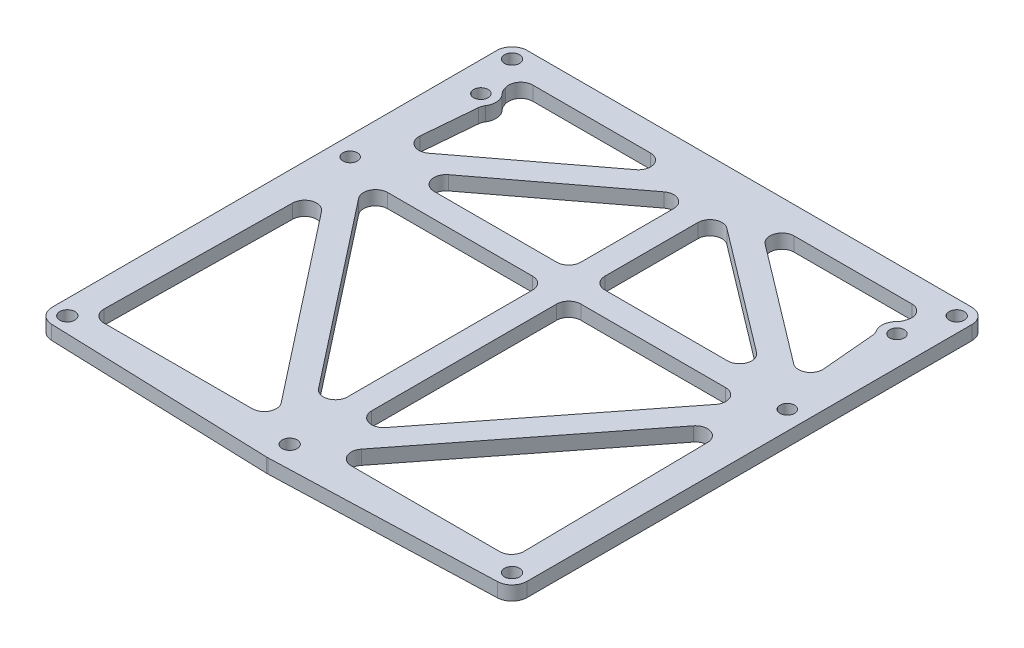
SolidWorks part; units mm, degrees
ref_plane "Front Plane" through (0, 0, 0) normal (0, 0, 1) x (1, 0, 0)
ref_plane "Top Plane" through (0, 0, 0) normal (0, 1, 0) x (1, 0, 0)
ref_plane "Right Plane" through (0, 0, 0) normal (1, 0, 0) x (0, 0, -1)
sketch "Sketch1" plane through (0, 0, 0) normal (0, 1, 0) x (1, 0, 0)
  line L0 (-43.8131, 37.2517) -> (-46.0269, 11.9483) construction
  line L1 (-50, -50) -> (50, -50) construction
  line L2 (-50, -50) -> (-50, 50) construction
  line L3 (-50, 50) -> (50, 50) construction
  line L4 (50, -50) -> (50, 50) construction
  line L5 (-50, -50) -> (50, 50) construction
  line L6 (-50, 50) -> (50, -50) construction
  line L7 (-46.0269, 11.9483) -> (-46.0269, 36.2261) construction
  line L8 (0, 0) -> (0, 21.5211) construction
  circle A0 centre (-46.825, -46.825) radius 1.5875
  circle A1 centre (-46.825, 46.825) radius 1.5875
  circle A2 centre (46.825, 46.825) radius 1.5875
  circle A3 centre (46.825, -46.825) radius 1.5875
  circle A4 centre (-43.8131, 37.2517) radius 1.524
  circle A5 centre (-46.0269, 11.9483) radius 1.524
  circle A6 centre (46.0269, 11.9483) radius 1.524
  circle A7 centre (43.8131, 37.2517) radius 1.524
  circle A8 centre (0, -46.825) radius 1.5875
  point P0 (0, 0)
  point P17 (0, 0)
  point P20 (-44.92, 24.6)
  dimension "D3" = 3.175
  dimension "D4" = 3.175
  dimension "D8" = 3.048
  dimension "D11" = 3.175
  dimension "D12" = 3.175
  dimension "D1" = 100
  dimension "D2" = 100
  dimension "D6" = 5
  dimension "D7" = 25.4
  dimension "D9" = 5.08
  dimension "D10" = 25.4
  dimension "D5" = 4
sketch "Sketch2" plane through (0, 0, 0) normal (0, 1, 0) x (1, 0, 0)
  line L0 (0.1615, -51.5848) -> (46.9326, -49.9982)
  line L1 (-0.1615, -51.5848) -> (-46.9326, -49.9982)
  line L2 (-46.825, 50) -> (46.825, 50)
  line L3 (50, 46.825) -> (50, -46.825)
  line L4 (-50, -46.825) -> (-50, 46.825)
  circle A0 centre (46.825, 46.825) radius 1.5875 construction
  circle A1 centre (43.8131, 37.2517) radius 1.524 construction
  circle A2 centre (46.0269, 11.9483) radius 1.524 construction
  circle A3 centre (46.825, -46.825) radius 1.5875 construction
  circle A4 centre (0, -46.825) radius 1.5875 construction
  circle A5 centre (-46.825, -46.825) radius 1.5875 construction
  circle A6 centre (-46.0269, 11.9483) radius 1.524 construction
  circle A7 centre (-43.8131, 37.2517) radius 1.524 construction
  circle A8 centre (-46.825, 46.825) radius 1.5875 construction
  circle A9 centre (46.825, 46.825) radius 1.5875
  circle A10 centre (43.8131, 37.2517) radius 1.524
  circle A11 centre (46.0269, 11.9483) radius 1.524
  circle A12 centre (46.825, -46.825) radius 1.5875
  circle A13 centre (0, -46.825) radius 1.5875
  circle A14 centre (-46.825, -46.825) radius 1.5875
  circle A15 centre (-46.0269, 11.9483) radius 1.524
  circle A16 centre (-43.8131, 37.2517) radius 1.524
  circle A17 centre (-46.825, 46.825) radius 1.5875
  circle A18 centre (-46.825, 46.825) radius 3.175
  circle A19 centre (-43.8131, 37.2517) radius 3.175
  circle A20 centre (-46.0269, 11.9483) radius 3.175
  circle A21 centre (-46.825, -46.825) radius 3.175
  circle A23 centre (46.825, -46.825) radius 3.175
  circle A24 centre (46.0269, 11.9483) radius 3.175
  circle A25 centre (43.8131, 37.2517) radius 3.175
  circle A26 centre (46.825, 46.825) radius 3.175
  circle A27 centre (0, -46.825) radius 4.7625
  dimension "D1" = 6.35
  dimension "D2" = 9.525
extrude "Boss-Extrude2" add sketch "Sketch2" along normal blind 2.9718 contours A27 L0 A23 L3 A26 L2 A18 L4 A21 L1 A19 A20 A24 A25 | A21 A14 | A27 A13 | A23 A12 | A24 A11 | A25 A10 | A26 A9 | A19 A16 | A18 A17 | A20 A15
sketch "Sketch3" plane through (0, 0, 0) normal (0, 1, 0) x (1, 0, 0)
  line L0 (-46.825, -46.825) -> (0, -46.825) construction
  line L1 (0, -46.825) -> (46.825, -46.825) construction
  line L2 (46.825, -46.825) -> (46.0269, 11.9483) construction
  line L3 (46.0269, 11.9483) -> (46.825, 46.825) construction
  line L4 (46.825, 46.825) -> (-46.825, 46.825) construction
  line L5 (-46.825, 46.825) -> (-46.0269, 11.9483) construction
  line L6 (-46.0269, 11.9483) -> (-46.825, -46.825) construction
  line L7 (0, -46.825) -> (-46.0269, 11.9483) construction
  line L8 (-46.0269, 11.9483) -> (46.0269, 11.9483) construction
  line L9 (46.0269, 11.9483) -> (0, -46.825) construction
  line L10 (43.8131, 37.2517) -> (46.825, 46.825) construction
  line L11 (-46.825, 46.825) -> (-43.8131, 37.2517) construction
  line L12 (46.0269, 11.9483) -> (0, 46.825) construction
  line L13 (0, 46.825) -> (-46.0269, 11.9483) construction
  line L14 (43.8131, 37.2517) -> (46.0269, 11.9483) construction
  line L15 (-46.0269, 11.9483) -> (-43.8131, 37.2517) construction
  line L16 (0, 11.9483) -> (0, -46.825) construction
  line L17 (0, 46.825) -> (0, 11.9483) construction
  line L18 (46.825, 49.365) -> (-46.825, 49.365)
  line L19 (-2.54, 46.825) -> (-2.54, 11.9483)
  line L20 (47.5609, 13.9728) -> (0, 50.0118)
  line L21 (0, 50.0118) -> (-47.5609, 13.9728)
  line L22 (-46.0269, 9.4083) -> (46.0269, 9.4083)
  line L23 (1.9998, -45.2589) -> (-44.0271, 13.5144)
  line L24 (-2.54, 11.9483) -> (-2.54, -46.825)
  line L25 (44.0271, 13.5144) -> (-1.9998, -45.2589)
  line L26 (0, -49.365) -> (49.3997, -49.365)
  line L27 (49.3997, -49.365) -> (48.5666, 11.9828)
  line L28 (-48.5666, 11.9828) -> (-49.3997, -49.365)
  line L29 (-49.3997, -49.365) -> (0, -49.365)
  line L30 (41.2828, 37.0303) -> (43.4965, 11.727)
  line L31 (48.5662, 11.8902) -> (49.3643, 46.7669)
  line L32 (46.236, 36.4894) -> (49.2479, 46.0627)
  line L33 (-49.2479, 46.0627) -> (-46.236, 36.4894)
  line L34 (-49.3643, 46.7669) -> (-48.5662, 11.8902)
  line L35 (-43.4965, 11.727) -> (-41.2828, 37.0303)
  line L36 (46.825, 44.285) -> (-46.825, 44.285)
  line L37 (2.54, 46.825) -> (2.54, 11.9483)
  line L38 (44.4929, 9.9239) -> (0, 43.6382)
  line L39 (0, 43.6382) -> (-44.4929, 9.9239)
  line L40 (-46.0269, 14.4883) -> (46.0269, 14.4883)
  line L41 (-1.9998, -48.3911) -> (-48.0266, 10.3823)
  line L42 (2.54, 11.9483) -> (2.54, -46.825)
  line L43 (48.0266, 10.3823) -> (1.9998, -48.3911)
  line L44 (0, -44.285) -> (44.2503, -44.285)
  line L45 (44.2503, -44.285) -> (43.4871, 11.9138)
  line L46 (-43.4871, 11.9138) -> (-44.2503, -44.285)
  line L47 (-44.2503, -44.285) -> (0, -44.285)
  line L48 (46.3435, 37.473) -> (48.5572, 12.1697)
  line L49 (43.4875, 12.0064) -> (44.2857, 46.8831)
  line L50 (41.3902, 38.014) -> (44.4021, 47.5873)
  line L51 (-44.4021, 47.5873) -> (-41.3902, 38.014)
  line L52 (-44.2857, 46.8831) -> (-43.4875, 12.0064)
  line L53 (-48.5572, 12.1697) -> (-46.3435, 37.473)
  circle A0 centre (-46.0269, 11.9483) radius 3.175 construction
  circle A1 centre (-43.8131, 37.2517) radius 3.175 construction
  circle A2 centre (-46.825, 46.825) radius 3.175 construction
  circle A3 centre (46.825, 46.825) radius 3.175 construction
  circle A4 centre (43.8131, 37.2517) radius 3.175 construction
  circle A5 centre (46.0269, 11.9483) radius 3.175 construction
  circle A6 centre (46.825, -46.825) radius 3.175 construction
  circle A7 centre (0, -46.825) radius 4.7625 construction
  circle A8 centre (-46.825, -46.825) radius 3.175 construction
  circle A9 centre (-46.0269, 11.9483) radius 3.175
  circle A10 centre (-43.8131, 37.2517) radius 3.175
  circle A11 centre (-46.825, 46.825) radius 3.175
  circle A12 centre (46.825, 46.825) radius 3.175
  circle A13 centre (43.8131, 37.2517) radius 3.175
  circle A14 centre (46.0269, 11.9483) radius 3.175
  circle A15 centre (46.825, -46.825) radius 3.175
  circle A16 centre (0, -46.825) radius 4.7625
  circle A17 centre (-46.825, -46.825) radius 3.175
  dimension "D1" = 2.54
  dimension "D2" = 2.54
  dimension "D3" = 2.54
  dimension "D4" = 2.54
extrude "Cut-Extrude1" cut sketch "Sketch3" along normal through all contours L46 L47 L41 | L24 L22 L23 | L22 L42 L25 | L44 L45 L43 | A13 L50 L36 L20 L30 | L37 L40 L38 | L39 L40 L19 | A10 L35 L21 L36 L51
fillet "Fillet1" radius 2.54 28 edges at (-5.2153, 1.4859, 44.285) (-43.5849, 1.4859, -4.7105) (-44.2503, 1.4859, 44.285) (43.5849, 1.4859, -4.7105) (5.2153, 1.4859, 44.285) (44.2503, 1.4859, 44.285) (2.54, 1.4859, -9.4083) (2.54, 1.4859, 39.462) (40.8116, 1.4859, -9.4083) (-40.8116, 1.4859, -9.4083) (-2.54, 1.4859, 39.462) (-43.3631, 1.4859, -44.285) (-41.9619, 1.4859, -39.8311) (41.9619, 1.4859, -39.8311) (43.3631, 1.4859, -44.285) (-2.54, 1.4859, -9.4083) (-2.54, 1.4859, -14.4883) (-2.54, 1.4859, -41.7135) (-38.4691, 1.4859, -14.4883) (38.4691, 1.4859, -14.4883) (2.54, 1.4859, -41.7135) (2.54, 1.4859, -14.4883) (-41.4488, 1.4859, -35.1325) (-42.9975, 1.4859, -17.4306) (-7.5577, 1.4859, -44.285) (7.5577, 1.4859, -44.285) (42.9975, 1.4859, -17.4306) (41.4488, 1.4859, -35.1325)
